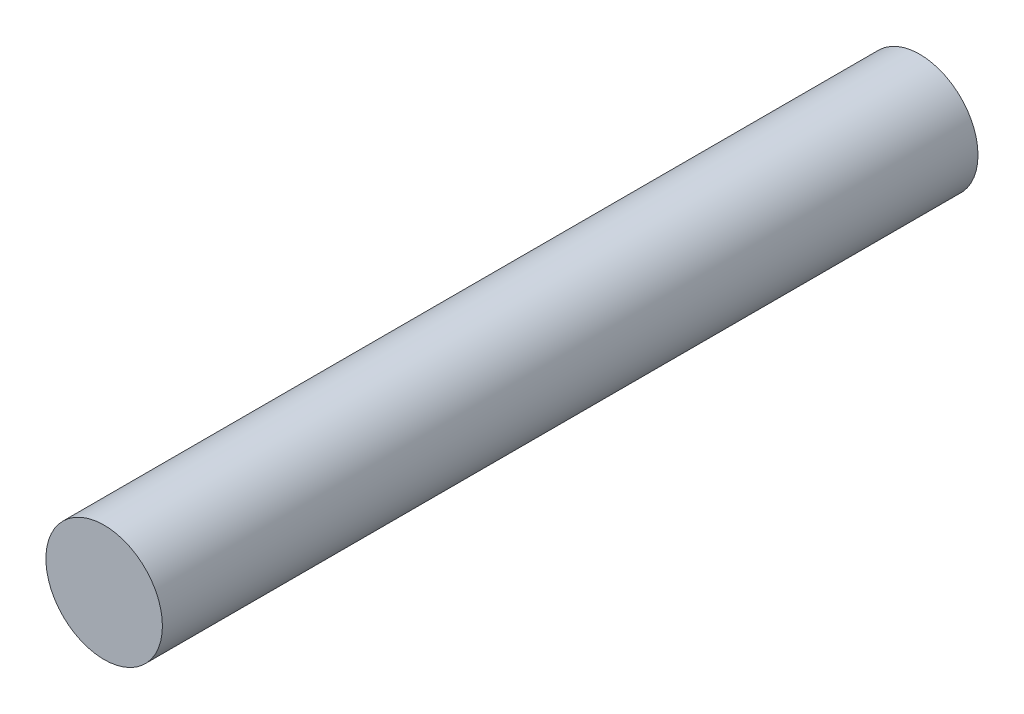
SolidWorks part; units mm, degrees
ref_plane "Front Plane" through (0, 0, 0) normal (0, 0, 1) x (1, 0, 0)
ref_plane "Top Plane" through (0, 0, 0) normal (0, 1, 0) x (1, 0, 0)
ref_plane "Right Plane" through (0, 0, 0) normal (1, 0, 0) x (0, 0, -1)
sketch "Sketch1" plane through (0, 0, 0) normal (0, 0, 1) x (1, 0, 0)
  circle A0 centre (0, 0) radius 3.175
  dimension "D1" = 6.35
extrude "Boss-Extrude1" add sketch "Sketch1" along normal mid plane 44.45
